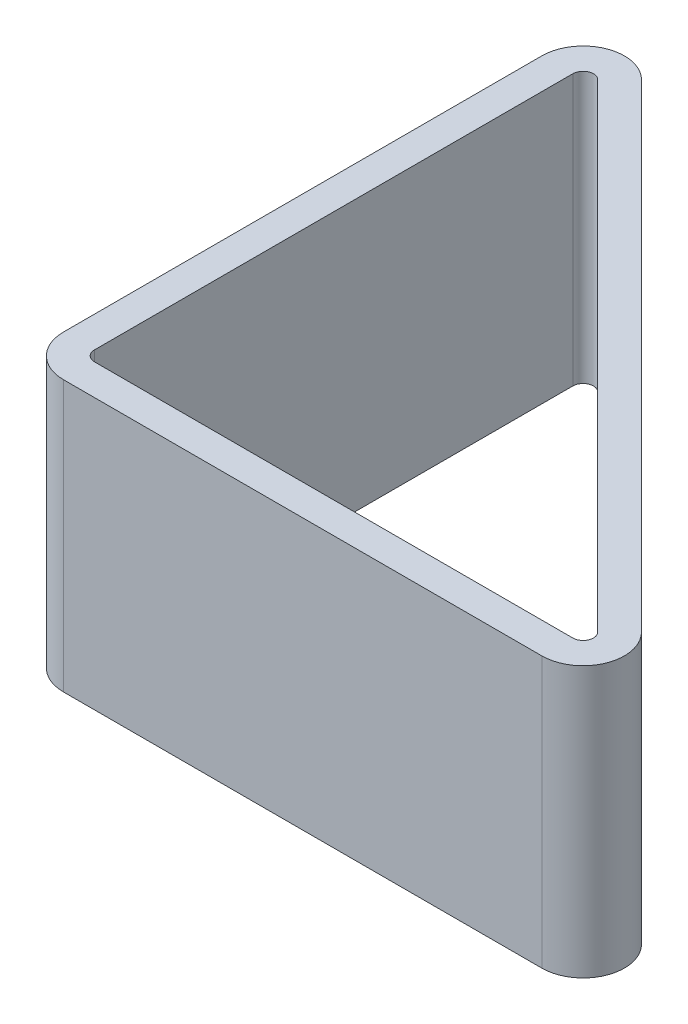
SolidWorks part; units mm, degrees
ref_plane "Front Plane" through (0, 0, 0) normal (0, 0, 1) x (1, 0, 0)
ref_plane "Top Plane" through (0, 0, 0) normal (0, 1, 0) x (1, 0, 0)
ref_plane "Right Plane" through (0, 0, 0) normal (1, 0, 0) x (0, 0, -1)
sketch "Sketch1" plane through (0, 0, 0) normal (0, 1, 0) x (1, 0, 0)
  line L0 (-46.7659, 36.6689) -> (-46.7659, -22.1869)
  line L1 (-41.6859, -27.2669) -> (17.1699, -27.2669)
  line L2 (20.762, -18.5948) -> (-38.0938, 40.261)
  line L3 (-42.9559, 36.6689) -> (-42.9559, -22.1869)
  line L4 (-41.6859, -23.4569) -> (17.1699, -23.4569)
  line L5 (18.068, -21.2889) -> (-40.7878, 37.5669)
  arc A0 (-38.0938, 40.261) -> (-46.7659, 36.6689) centre (-41.6859, 36.6689) ccw
  arc A1 (-41.6859, -27.2669) -> (-46.7659, -22.1869) centre (-41.6859, -22.1869) cw
  arc A2 (17.1699, -27.2669) -> (20.762, -18.5948) centre (17.1699, -22.1869) ccw
  arc A3 (-41.6859, -23.4569) -> (-42.9559, -22.1869) centre (-41.6859, -22.1869) cw
  arc A4 (17.1699, -23.4569) -> (18.068, -21.2889) centre (17.1699, -22.1869) ccw
  arc A5 (-40.7878, 37.5669) -> (-42.9559, 36.6689) centre (-41.6859, 36.6689) ccw
  point P5 (-46.7659, 48.9331)
  point P8 (-46.7659, -27.2669)
  point P11 (29.4341, -27.2669)
  dimension "D3" = 5.08
  dimension "D1" = 76.2
  dimension "D2" = 76.2
  dimension "D4" = 3.81
extrude "Extrude1" add sketch "Sketch1" along normal blind 33.274
